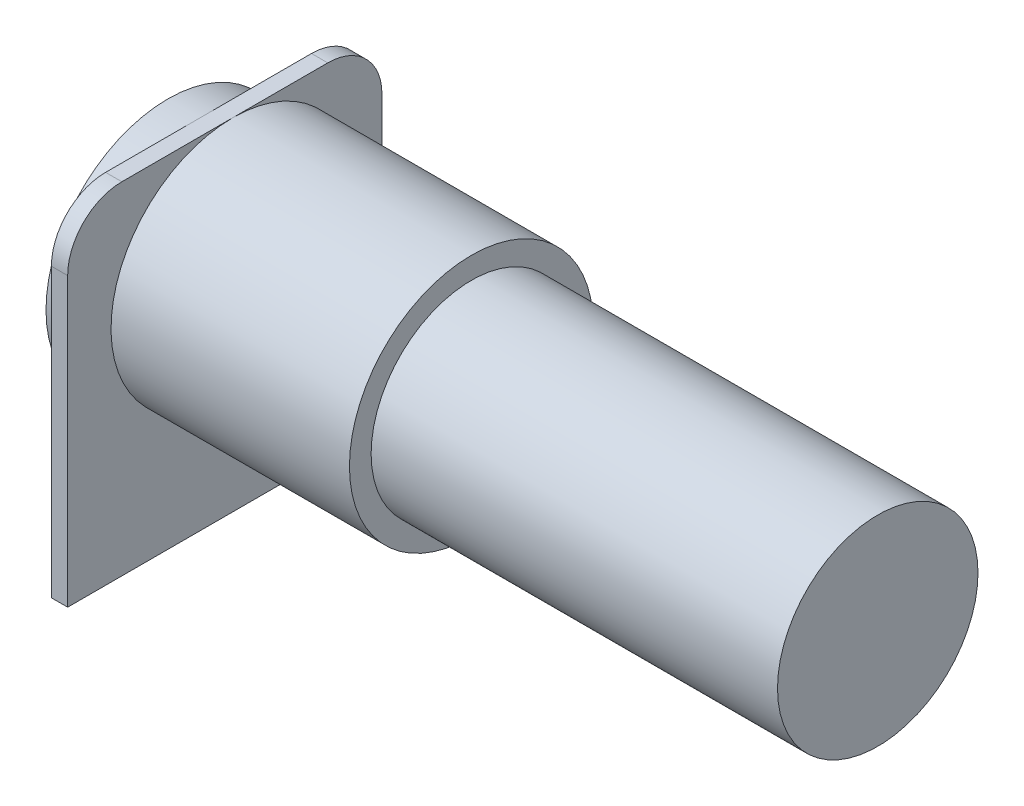
SolidWorks part; units mm, degrees
ref_plane "Front Plane" through (0, 0, 0) normal (0, 0, 1) x (1, 0, 0)
ref_plane "Top Plane" through (0, 0, 0) normal (0, 1, 0) x (1, 0, 0)
ref_plane "Right Plane" through (0, 0, 0) normal (1, 0, 0) x (0, 0, -1)
sketch "Sketch1" plane through (0, 0, 0) normal (1, 0, 0) x (0, 0, -1)
  line L1 (-10, -1.2225) -> (-48, -1.2225)
  line L2 (0, -11.2225) -> (0, -64.2225)
  line L3 (0, -64.2225) -> (-58, -64.2225)
  line L4 (-58, -11.2225) -> (-58, -64.2225)
  arc A0 (-10, -1.2225) -> (0, -11.2225) centre (-10, -11.2225) cw
  arc A1 (-48, -1.2225) -> (-58, -11.2225) centre (-48, -11.2225) ccw
  point P6 (0, -1.2225)
  point P9 (-58, -1.2225)
  dimension "D3" = 10
  dimension "D1" = 58
  dimension "D2" = 63
extrude "Boss-Extrude1" add sketch "Sketch1" along normal blind 3
sketch "Sketch2" plane through (3, 0, 0) normal (1, 0, 0) x (0, 0, -1)
  line L0 (-10, -1.2225) -> (-48, -1.2225) construction
  line L1 (0, -64.2225) -> (0, -11.2225) construction
  circle A0 centre (-27.5, -23.7225) radius 22.5
  dimension "D1" = 45
  dimension "D2" = 22.5
  dimension "D3" = 27.5
extrude "Boss-Extrude2" add sketch "Sketch2" along normal blind 44
sketch "Sketch3" plane through (47, 0, 0) normal (1, 0, 0) x (0, 0, -1)
  circle A0 centre (-27.5, -23.7225) radius 18.5
  dimension "D1" = 37
extrude "Boss-Extrude3" add sketch "Sketch3" along normal blind 75
sketch "Sketch4" plane through (0, 0, 0) normal (-1, 0, 0) x (0, 0, 1)
  line L0 (10, -1.2225) -> (48, -1.2225) construction
  line L1 (58, -11.2225) -> (58, -64.2225) construction
  circle A0 centre (30.5, -23.7225) radius 22.5
  dimension "D1" = 45
  dimension "D2" = 22.5
  dimension "D3" = 27.5
extrude "Boss-Extrude4" add sketch "Sketch4" along normal blind 6
sketch "Sketch5" plane through (-6, 0, 0) normal (-1, 0, 0) x (0, 0, 1)
  circle A0 centre (30.5, -23.7225) radius 3
  dimension "D1" = 6
extrude "Boss-Extrude5" add sketch "Sketch5" along normal blind 7.5
